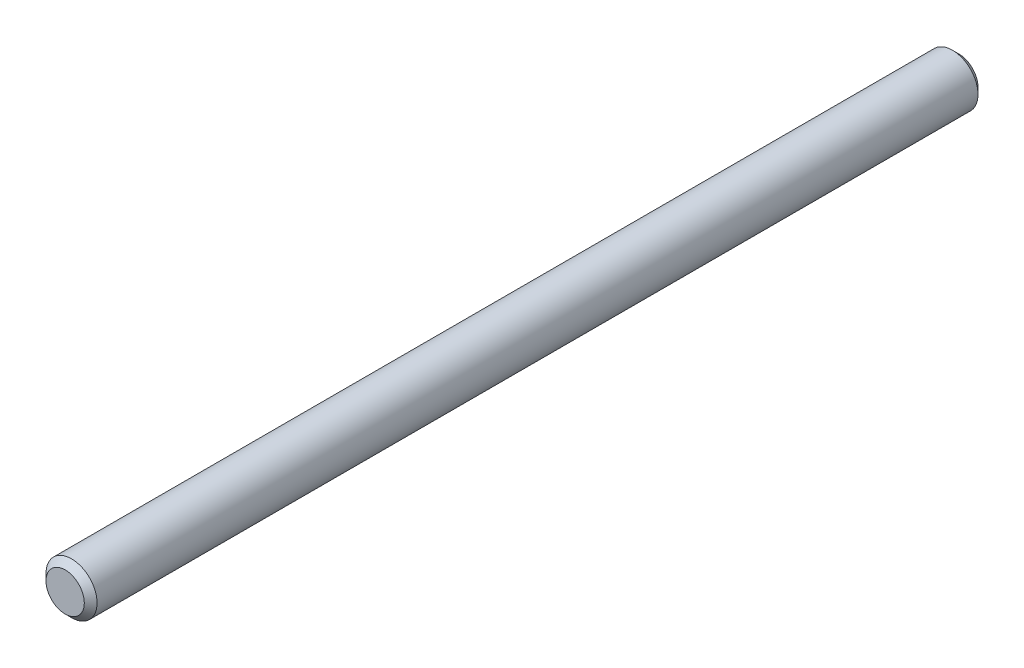
SolidWorks part; units mm, degrees
ref_plane "Front Plane" through (0, 0, 0) normal (0, 0, 1) x (1, 0, 0)
ref_plane "Top Plane" through (0, 0, 0) normal (0, 1, 0) x (1, 0, 0)
ref_plane "Right Plane" through (0, 0, 0) normal (1, 0, 0) x (0, 0, -1)
sketch "Sketch1" plane through (0, 0, 0) normal (0, 0, 1) x (1, 0, 0)
  circle A0 centre (0, 0) radius 4
  dimension "D1" = 8
extrude "Boss-Extrude1" add sketch "Sketch1" along normal blind 140
chamfer "Chamfer1" distance 1 angle 45 2 edges at (4, 0, 140) (4, 0, 0)
equation "\"L\"=140"
